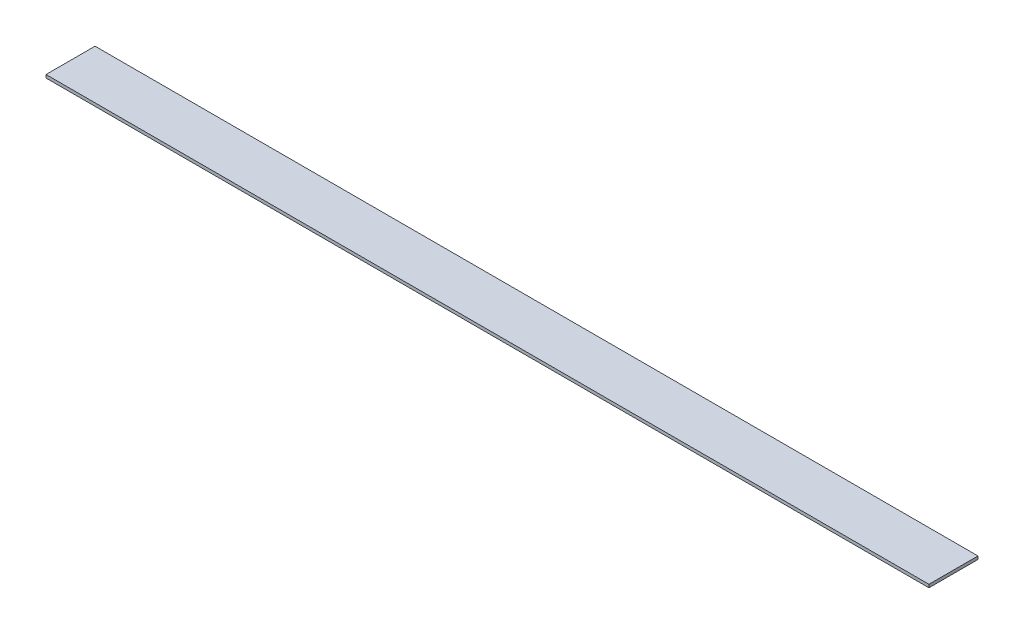
SolidWorks part; units mm, degrees
material "Polyurethane Foam Flexible"
ref_plane "Front Plane" through (0, 0, 0) normal (0, 0, 1) x (1, 0, 0)
ref_plane "Top Plane" through (0, 0, 0) normal (0, 1, 0) x (1, 0, 0)
ref_plane "Right Plane" through (0, 0, 0) normal (1, 0, 0) x (0, 0, -1)
sketch "Sketch1" plane through (0, 0, 0) normal (0, 1, 0) x (1, 0, 0)
  line L1 (-457.2, -25.4) -> (457.2, -25.4)
  line L2 (-457.2, -25.4) -> (-457.2, 25.4)
  line L3 (-457.2, 25.4) -> (457.2, 25.4)
  line L4 (457.2, -25.4) -> (457.2, 25.4)
  line L5 (-457.2, -25.4) -> (457.2, 25.4) construction
  line L6 (-457.2, 25.4) -> (457.2, -25.4) construction
  point P0 (0, 0)
  dimension "D1" = 50.8
  dimension "D2" = 914.4
extrude "Boss-Extrude1" add sketch "Sketch1" along normal blind 3.175
